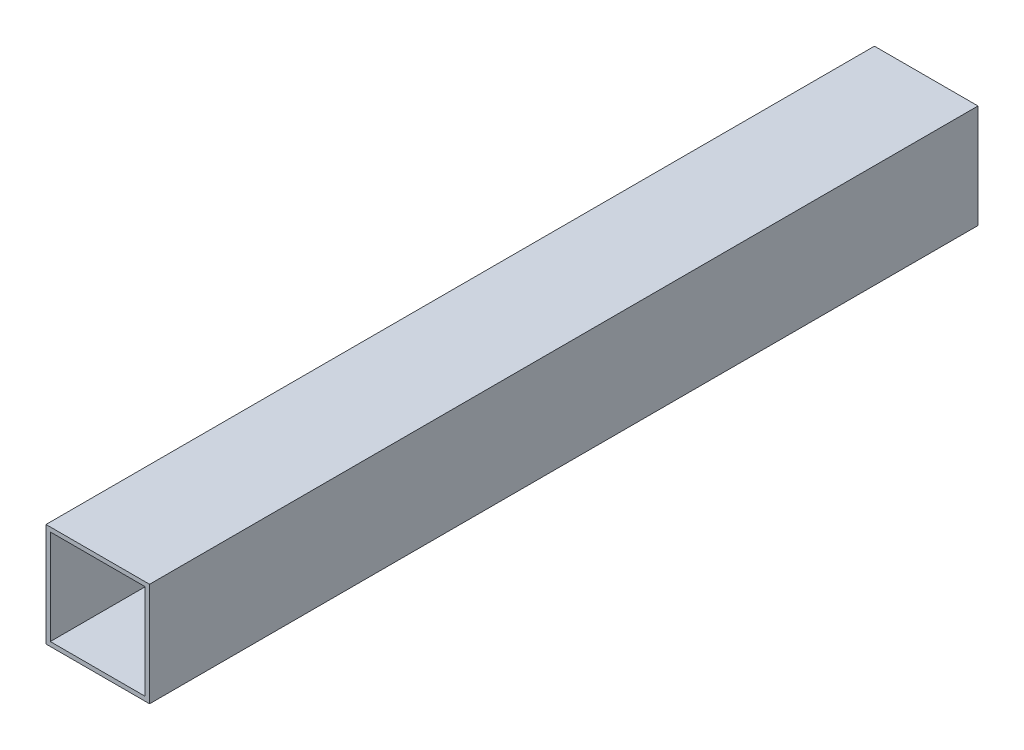
SolidWorks part; units mm, degrees
material "Plain Carbon Steel"
ref_plane "Front Plane" through (0, 0, 0) normal (0, 0, 1) x (1, 0, 0)
ref_plane "Top Plane" through (0, 0, 0) normal (0, 1, 0) x (1, 0, 0)
ref_plane "Right Plane" through (0, 0, 0) normal (1, 0, 0) x (0, 0, -1)
sketch "Sketch2" plane through (0, 0, 0) normal (0, 0, 1) x (1, 0, 0)
  line L0 (0, 19.05) -> (1.5875, 19.05) construction
  line L1 (0, 0) -> (38.1, 0)
  line L2 (0, 0) -> (0, 38.1)
  line L3 (0, 38.1) -> (38.1, 38.1)
  line L4 (38.1, 0) -> (38.1, 38.1)
  line L5 (1.5875, 1.5875) -> (36.5125, 1.5875)
  line L6 (1.5875, 1.5875) -> (1.5875, 36.5125)
  line L7 (1.5875, 36.5125) -> (36.5125, 36.5125)
  line L8 (36.5125, 1.5875) -> (36.5125, 36.5125)
  line L9 (19.05, 36.5125) -> (19.05, 38.1) construction
  line L10 (36.5125, 19.05) -> (38.1, 19.05) construction
  line L11 (19.05, 0) -> (19.05, 1.5875) construction
  dimension "D1" = 38.1
  dimension "D2" = 1.5875
  dimension "D3" = 38.1
extrude "Boss-Extrude1" add sketch "Sketch2" along normal blind 304.8
